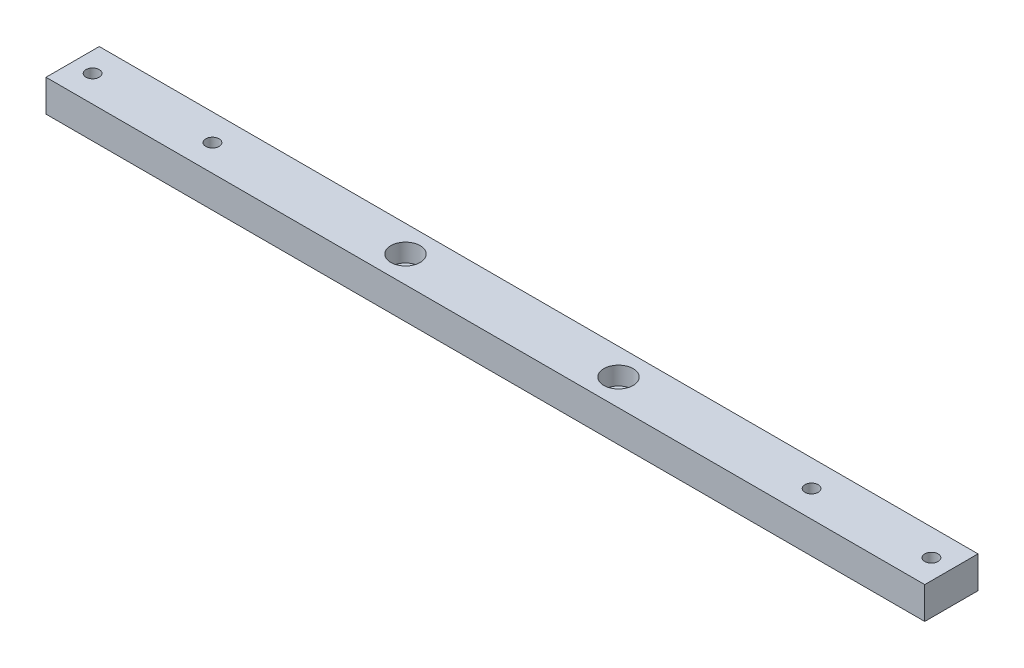
SolidWorks part; units mm, degrees
material "6061"
ref_plane "前视" through (0, 0, 0) normal (0, 0, 1) x (1, 0, 0)
ref_plane "上视" through (0, 0, 0) normal (0, 1, 0) x (1, 0, 0)
ref_plane "右视" through (0, 0, 0) normal (1, 0, 0) x (0, 0, -1)
sketch "草图1" plane through (0, 0, 0) normal (0, 1, 0) x (1, 0, 0)
  line L1 (-165, -10) -> (165, -10)
  line L2 (-165, -10) -> (-165, 10)
  line L3 (-165, 10) -> (165, 10)
  line L4 (165, -10) -> (165, 10)
  line L5 (-165, -10) -> (165, 10) construction
  line L6 (-165, 10) -> (165, -10) construction
  point P0 (0, 0)
  dimension "D1" = 330
  dimension "D2" = 20
extrude "凸台-拉伸1" add sketch "草图1" along normal blind 12
hole_wizard "M6 螺纹孔1" positions "草图3" profile "草图2" tap size "M6" standard "Gb"
sketch "草图3" plane through (0, 12, 0) normal (0, 1, 0) x (1, 0, 0)
  line L0 (-165, 0) -> (0, 0) construction
  line L1 (-165, 10) -> (-165, -10) construction
  line L2 (0, 0) -> (0, -10) construction
  line L3 (-165, -10) -> (165, -10) construction
  point P0 (-157.5, 0)
  point P2 (-112.5, 0)
  point P18 (112.5, 0)
  point P19 (157.5, 0)
  dimension "D1" = 45
  dimension "D2" = 270
sketch "草图2" plane through (-157.5, 12, 0) normal (1, 0, 0) x (0, 0, 1)
  line L0 (0, 0) -> (0, 16.5022)
  line L1 (0, 16.5022) -> (2.5, 15)
  line L2 (2.5, 15) -> (2.5, 0)
  line L5 (2.5, 0) -> (0, 0)
  line L10 (0, 16.5022) -> (-2.5, 15) construction
  line L11 (0, -6.35) -> (0, 107.95) construction
  dimension "螺纹孔钻头直径" = 5
  dimension "螺纹孔钻头深度" = 15
  dimension "导头角度" = 118
cosmetic thread "孔螺蚊线1" parameters "D1"=12, "D2"=6
cosmetic thread "孔螺蚊线2" parameters "D1"=12, "D2"=6
cosmetic thread "孔螺蚊线3" parameters "D1"=12, "D2"=6
cosmetic thread "孔螺蚊线4" parameters "D1"=12, "D2"=6
hole_wizard "打孔尺寸根据内六角圆柱头螺钉的类型1" positions "草图5" profile "草图4" counterbore size "M6" standard "Gb" end condition through all
sketch "草图5" plane through (0, 12, 0) normal (0, 1, 0) x (1, 0, 0)
  line L0 (0, 10) -> (0, -4.8363) construction
  line L1 (165, 10) -> (-165, 10) construction
  point P0 (-40, 0)
  point P10 (40, 0)
  dimension "D1" = 80
sketch "草图4" plane through (-40, 12, 0) normal (1, 0, 0) x (0, 0, 1)
  line L0 (0, 0) -> (0, 12)
  line L1 (0, 12) -> (3.3, 12)
  line L3 (3.3, 12) -> (3.3, 6.8)
  line L4 (3.3, 6.8) -> (5.5, 6.8)
  line L5 (5.5, 6.8) -> (5.5, 0)
  line L7 (5.5, 0) -> (0, 0)
  line L11 (0, -6.35) -> (0, 107.95) construction
  dimension "通孔孔直径" = 6.6
  dimension "通孔孔深度" = 12
  dimension "柱形沉头孔直径" = 11
  dimension "柱形沉头孔深度" = 6.8
